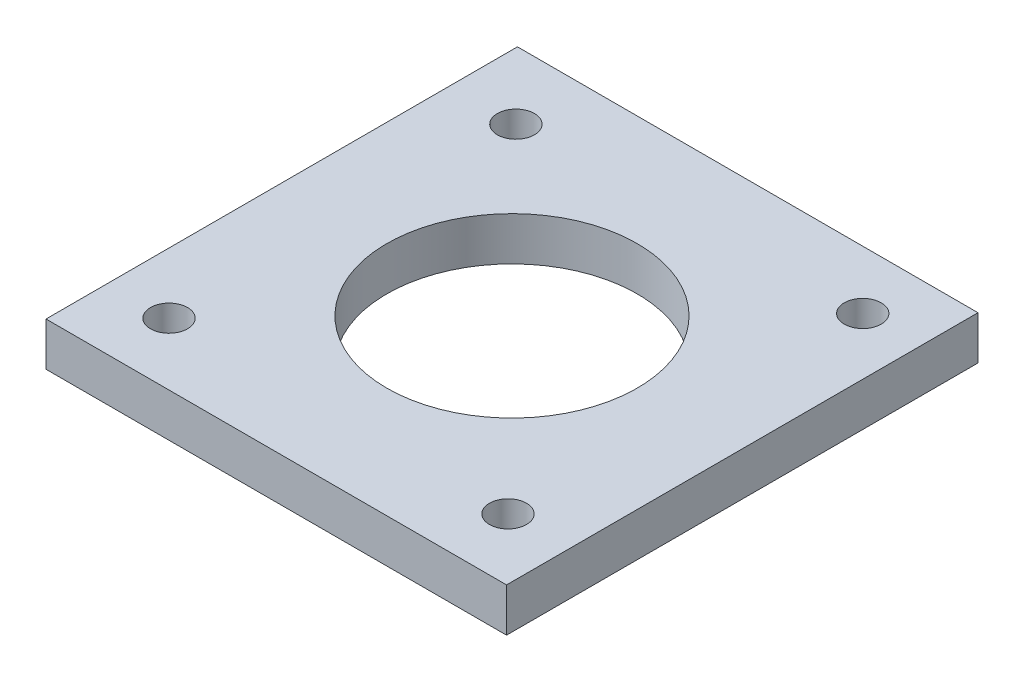
SolidWorks part; units mm, degrees
ref_plane "Front Plane" through (0, 0, 0) normal (0, 0, 1) x (1, 0, 0)
ref_plane "Top Plane" through (0, 0, 0) normal (0, 1, 0) x (1, 0, 0)
ref_plane "Right Plane" through (0, 0, 0) normal (1, 0, 0) x (0, 0, -1)
sketch "Sketch2" plane through (0, 0, 0) normal (0, 1, 0) x (1, 0, 0)
  line L1 (-21.15, -21.65) -> (21.15, -21.65)
  line L2 (-21.15, -21.65) -> (-21.15, 21.65)
  line L3 (-21.15, 21.65) -> (21.15, 21.65)
  line L4 (21.15, -21.65) -> (21.15, 21.65)
  line L5 (-21.15, -21.65) -> (21.15, 21.65) construction
  line L6 (-21.15, 21.65) -> (21.15, -21.65) construction
  circle A0 centre (-15.0694, 15.4256) radius 1.7
  circle A1 centre (15.9184, 16.2948) radius 1.7
  circle A2 centre (15.5664, -15.9344) radius 1.7
  circle A3 centre (-15.5664, -15.9344) radius 1.7
  circle A4 centre (0, 0) radius 11.5
  point P0 (0, 0)
  dimension "D4" = 3.4
  dimension "D5" = 23
  dimension "D1" = 43.3
  dimension "D2" = 42.3
  dimension "D3" = 31
extrude "Boss-Extrude1" add sketch "Sketch2" along normal blind 4
ref_plane "Plane1" through (-21.15, 0, -21.65) normal (-1, 0, 0) x (0, 0, 1)
sketch "Sketch6" plane through (0, 0, -21.65) normal (0, 0, -1) x (-1, 0, 0)
  line L0 (0, 0) -> (21.15, 0)
  line L1 (21.15, -11.6325) -> (21.15, 11.6325) construction
  line L5 (0, 0) -> (-21.15, 0)
